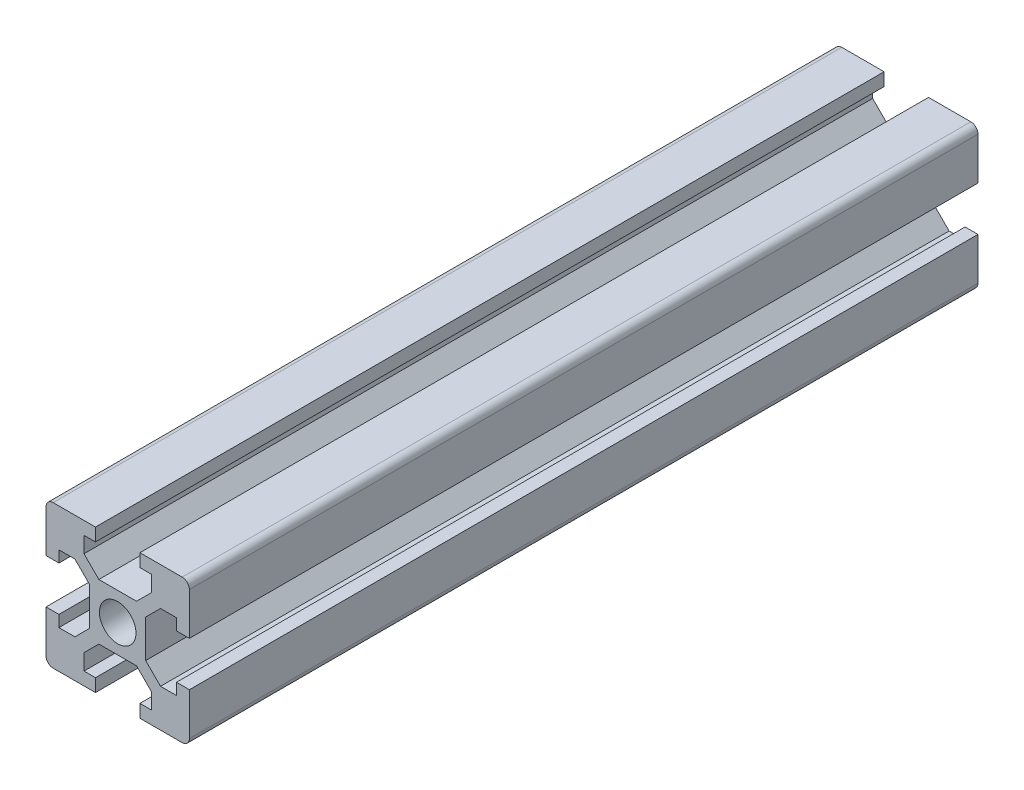
SolidWorks part; units mm, degrees
ref_plane "前视基准面" through (0, 0, 0) normal (0, 0, 1) x (1, 0, 0)
ref_plane "上视基准面" through (0, 0, 0) normal (0, 1, 0) x (1, 0, 0)
ref_plane "右视基准面" through (0, 0, 0) normal (1, 0, 0) x (0, 0, -1)
sketch "草图1" plane through (0, 0, 0) normal (0, 0, 1) x (1, 0, 0)
  line L0 (4.6219, 1.9053) -> (6.6947, 3.9781)
  line L1 (-8.0053, 8.0053) -> (-1.1053, 8.0053)
  line L2 (-8.0053, 8.0053) -> (-8.0053, 1.1053)
  line L3 (-8.0053, -11.9947) -> (-1.1053, -11.9947)
  line L4 (11.9947, 8.0053) -> (11.9947, 1.1053)
  line L5 (-8.0053, 8.0053) -> (11.9947, -11.9947) construction
  line L6 (5.8947, 0.6325) -> (7.9675, 2.7053)
  line L7 (-0.6325, -5.8947) -> (4.6219, -5.8947)
  line L8 (-1.9053, -4.6219) -> (-1.9053, 0.6325)
  line L9 (-0.6325, 1.9053) -> (4.6219, 1.9053)
  line L10 (5.8947, -4.6219) -> (5.8947, 0.6325)
  line L11 (-2.53, -6.5195) -> (5.8947, 1.9053) construction
  line L12 (-2.53, 2.53) -> (5.8947, -5.8947) construction
  line L13 (7.9675, 2.7053) -> (10.1947, 2.7053)
  line L14 (6.6947, 3.9781) -> (6.6947, 6.2053)
  line L15 (6.6947, 6.2053) -> (5.0947, 6.2053)
  line L16 (5.0947, 6.2053) -> (5.0947, 8.0053)
  line L17 (10.1947, 2.7053) -> (10.1947, 1.1053)
  line L18 (10.1947, 1.1053) -> (11.9947, 1.1053)
  line L19 (1.9947, -1.9947) -> (1.9947, 14.4959) construction
  line L20 (-6.2053, 1.1053) -> (-8.0053, 1.1053)
  line L21 (-6.2053, 2.7053) -> (-6.2053, 1.1053)
  line L22 (-1.9053, 0.6325) -> (-3.9781, 2.7053)
  line L23 (-3.9781, 2.7053) -> (-6.2053, 2.7053)
  line L24 (-2.7053, 3.9781) -> (-2.7053, 6.2053)
  line L25 (-0.6325, 1.9053) -> (-2.7053, 3.9781)
  line L26 (-2.7053, 6.2053) -> (-1.1053, 6.2053)
  line L27 (-1.1053, 6.2053) -> (-1.1053, 8.0053)
  line L28 (1.9947, -1.9947) -> (-12.4459, -1.9947) construction
  line L29 (-1.9053, -4.6219) -> (-3.9781, -6.6947)
  line L30 (-0.6325, -5.8947) -> (-2.7053, -7.9675)
  line L31 (4.6219, -5.8947) -> (6.6947, -7.9675)
  line L32 (5.8947, -4.6219) -> (7.9675, -6.6947)
  line L33 (-6.2053, -5.0947) -> (-8.0053, -5.0947)
  line L34 (10.1947, -5.0947) -> (11.9947, -5.0947)
  line L35 (-1.1053, -10.1947) -> (-1.1053, -11.9947)
  line L36 (5.0947, -10.1947) -> (5.0947, -11.9947)
  line L37 (-2.7053, -10.1947) -> (-1.1053, -10.1947)
  line L38 (-2.7053, -7.9675) -> (-2.7053, -10.1947)
  line L39 (-3.9781, -6.6947) -> (-6.2053, -6.6947)
  line L40 (-6.2053, -6.6947) -> (-6.2053, -5.0947)
  line L41 (10.1947, -6.6947) -> (10.1947, -5.0947)
  line L42 (6.6947, -10.1947) -> (5.0947, -10.1947)
  line L43 (6.6947, -7.9675) -> (6.6947, -10.1947)
  line L44 (7.9675, -6.6947) -> (10.1947, -6.6947)
  line L45 (11.9947, -5.0947) -> (11.9947, -11.9947)
  line L46 (5.0947, 8.0053) -> (11.9947, 8.0053)
  line L47 (-8.0053, -5.0947) -> (-8.0053, -11.9947)
  line L48 (5.0947, -11.9947) -> (11.9947, -11.9947)
  circle A0 centre (1.9947, -1.9947) radius 2.55
  point P0 (0, 0)
  point P6 (1.9947, -1.9947)
  dimension "D4" = 5.1
  dimension "D1" = 20
  dimension "D2" = 20
  dimension "D3" = 7.8
  dimension "D5" = 6.2
  dimension "D6" = 9.4
  dimension "D7" = 0.9
  dimension "D8" = 1.8
extrude "凸台-拉伸1" add sketch "草图1" along normal blind 110
fillet "圆角1" radius 1 4 edges at (11.9947, -11.9947, 55) (-8.0053, -11.9947, 55) (11.9947, 8.0053, 55) (-8.0053, 8.0053, 55)
